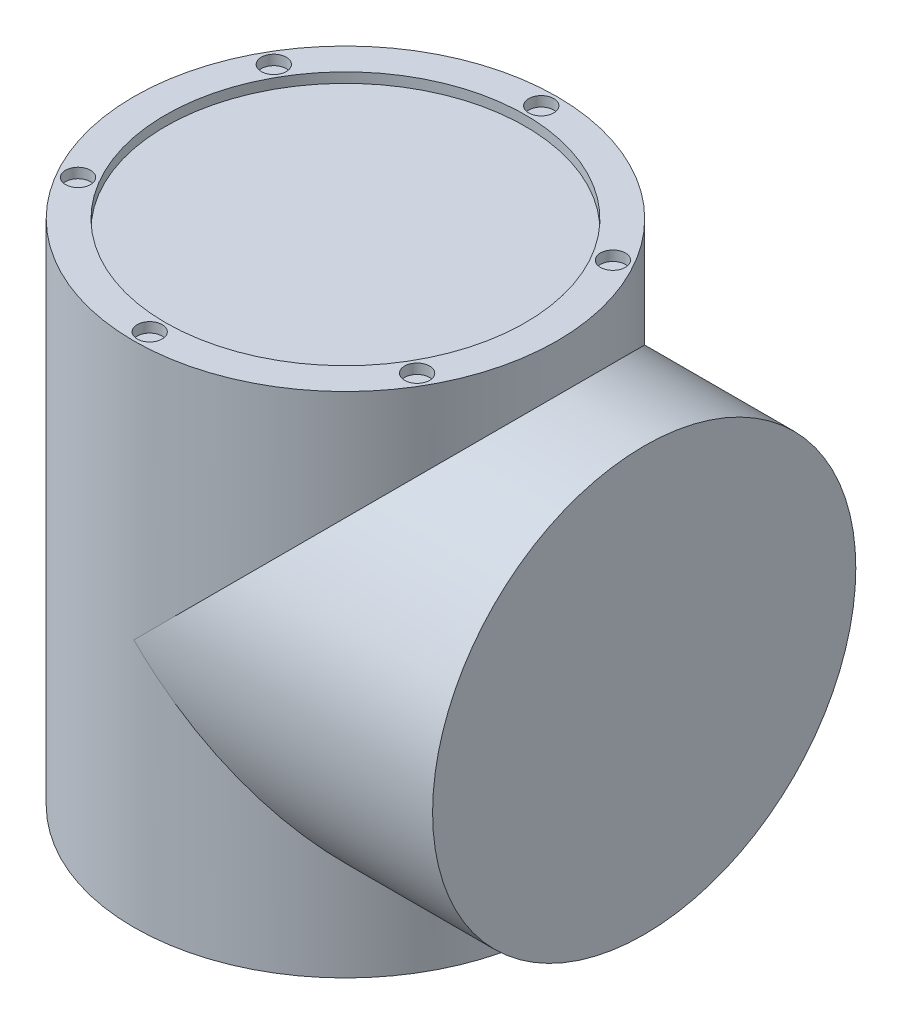
SolidWorks part; units mm, degrees
ref_plane "Alzado" through (0, 0, 0) normal (0, 0, 1) x (1, 0, 0)
ref_plane "Planta" through (0, 0, 0) normal (0, 1, 0) x (1, 0, 0)
ref_plane "Vista lateral" through (0, 0, 0) normal (1, 0, 0) x (0, 0, -1)
sketch "Croquis1" plane through (0, 0, 0) normal (0, 1, 0) x (1, 0, 0)
  circle A0 centre (0, 0) radius 42.5
  dimension "D1" = 85
extrude "Saliente-Extruir1" add sketch "Croquis1" along normal blind 100
sketch "Croquis2" plane through (0, 0, 0) normal (1, 0, 0) x (0, 0, -1)
  line L0 (42.5, 100) -> (-42.5, 100) construction
  line L2 (42.5, 0) -> (42.5, 100) construction
  circle A0 centre (0, 50) radius 42.5
  point P2 (0, 0)
  point P5 (0, 0)
  point P7 (-48.8949, 38.6672)
  dimension "D1" = 85
  dimension "D2" = 50
  dimension "D3" = 42.5
extrude "Saliente-Extruir2" add sketch "Croquis2" along normal blind 60
sketch "Croquis3" plane through (0, 100, 0) normal (0, 1, 0) x (1, 0, 0)
  circle A0 centre (0, 0) radius 42.5
  circle A1 centre (0, 0) radius 36.1436
  circle A2 centre (0, 39.3191) radius 2.5082
  circle A3 centre (34.0513, 19.6595) radius 2.5082
  circle A4 centre (34.0513, -19.6595) radius 2.5082
  circle A5 centre (0, -39.3191) radius 2.5082
  circle A6 centre (-34.0513, -19.6595) radius 2.5082
  circle A7 centre (-34.0513, 19.6595) radius 2.5082
  point P18 (0, 0)
  dimension "D1" = 6
extrude "Saliente-Extruir3" add sketch "Croquis3" along normal blind 2
